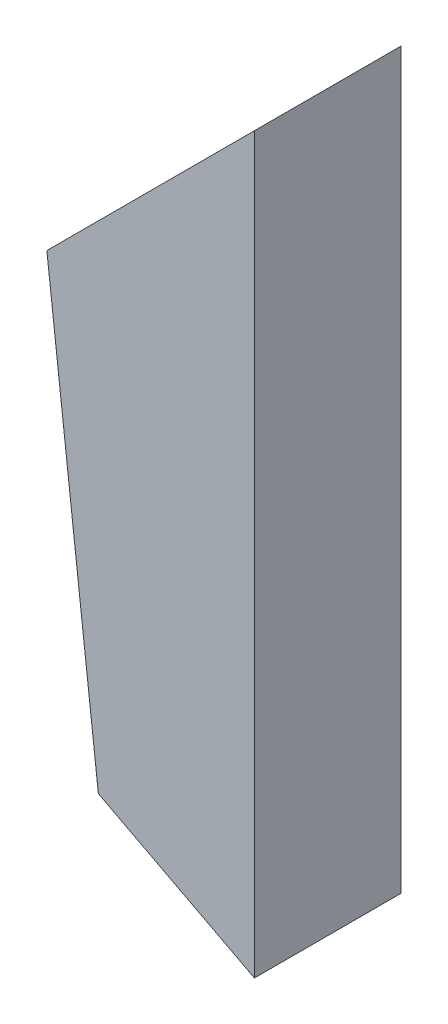
SolidWorks part; units mm, degrees
ref_plane "Front" through (0, 0, 0) normal (0, 0, 1) x (1, 0, 0)
ref_plane "Top" through (0, 0, 0) normal (0, 1, 0) x (1, 0, 0)
ref_plane "Right" through (0, 0, 0) normal (1, 0, 0) x (0, 0, -1)
sketch "Sketch1" plane through (0, 0, 0) normal (0, 0, 1) x (1, 0, 0)
  line L0 (0, 0) -> (14.1421, 14.1421)
  line L1 (14.1421, 14.1421) -> (14.1421, -35.8579)
  line L2 (14.1421, -35.8579) -> (3.51, -30.2939)
  line L3 (3.51, -30.2939) -> (0, 0)
  dimension "D1" = 50
  dimension "D2" = 20
  dimension "D3" = 12
  dimension "D4" = 30.4966
extrude "Boss-Extrude1" add sketch "Sketch1" along normal blind 10
